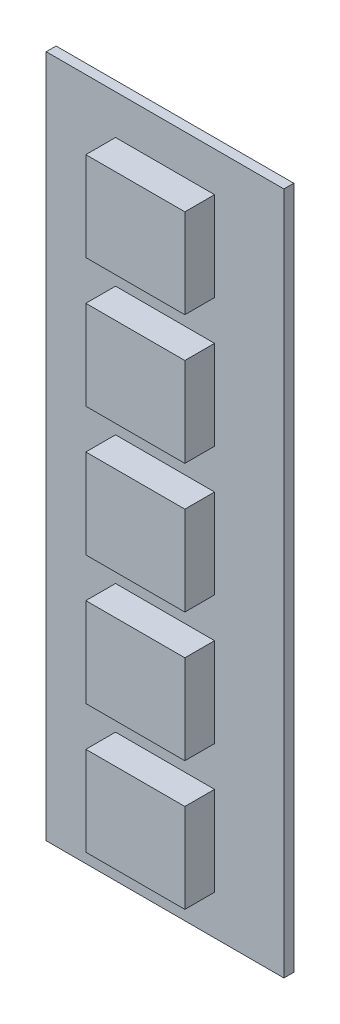
SolidWorks part; units mm, degrees
ref_plane "Plan de face" through (0, 0, 0) normal (0, 0, 1) x (1, 0, 0)
ref_plane "Plan de dessus" through (0, 0, 0) normal (0, 1, 0) x (1, 0, 0)
ref_plane "Plan de droite" through (0, 0, 0) normal (1, 0, 0) x (0, 0, -1)
sketch "Esquisse1" plane through (0, 0, 0) normal (0, 0, 1) x (1, 0, 0)
  line L1 (-12, 35.2632) -> (0, 35.2632)
  line L2 (-12, 35.2632) -> (-12, 0.7632)
  line L3 (-12, 0.7632) -> (0, 0.7632)
  line L4 (0, 35.2632) -> (0, 0.7632)
  dimension "D1" = 12
  dimension "D2" = 34.5
extrude "Boss.-Extru.1" add sketch "Esquisse1" along normal blind 0.5
sketch "Esquisse2" plane through (0, 0, 0.5) normal (0, 0, 1) x (1, 0, 0)
  line L0 (0, 35.2632) -> (-12, 35.2632) construction
  line L1 (-8.5, 33.2632) -> (-3.5, 33.2632)
  line L2 (-8.5, 33.2632) -> (-8.5, 28.7632)
  line L3 (-8.5, 28.7632) -> (-3.5, 28.7632)
  line L4 (-3.5, 33.2632) -> (-3.5, 28.7632)
  line L5 (-8.5, 26.7632) -> (-8.5, 22.2632)
  line L6 (-8.5, 26.7632) -> (-3.5, 26.7632)
  line L7 (-3.5, 26.7632) -> (-3.5, 22.2632)
  line L8 (-8.5, 22.2632) -> (-3.5, 22.2632)
  line L9 (-8.5, 20.2632) -> (-8.5, 15.7632)
  line L10 (-8.5, 20.2632) -> (-3.5, 20.2632)
  line L11 (-3.5, 20.2632) -> (-3.5, 15.7632)
  line L12 (-8.5, 15.7632) -> (-3.5, 15.7632)
  line L13 (-8.5, 13.7632) -> (-8.5, 9.2632)
  line L14 (-8.5, 13.7632) -> (-3.5, 13.7632)
  line L15 (-3.5, 13.7632) -> (-3.5, 9.2632)
  line L16 (-8.5, 9.2632) -> (-3.5, 9.2632)
  line L17 (-8.5, 7.2632) -> (-8.5, 2.7632)
  line L18 (-8.5, 7.2632) -> (-3.5, 7.2632)
  line L19 (-3.5, 7.2632) -> (-3.5, 2.7632)
  line L20 (-8.5, 2.7632) -> (-3.5, 2.7632)
  point P6 (-6, 33.2632)
  point P7 (-6, 35.2632)
  dimension "D1" = 5
  dimension "D2" = 2
  dimension "D4" = 4.5
  dimension "D3" = 5
extrude "Boss.-Extru.2" add sketch "Esquisse2" along normal blind 1.5
